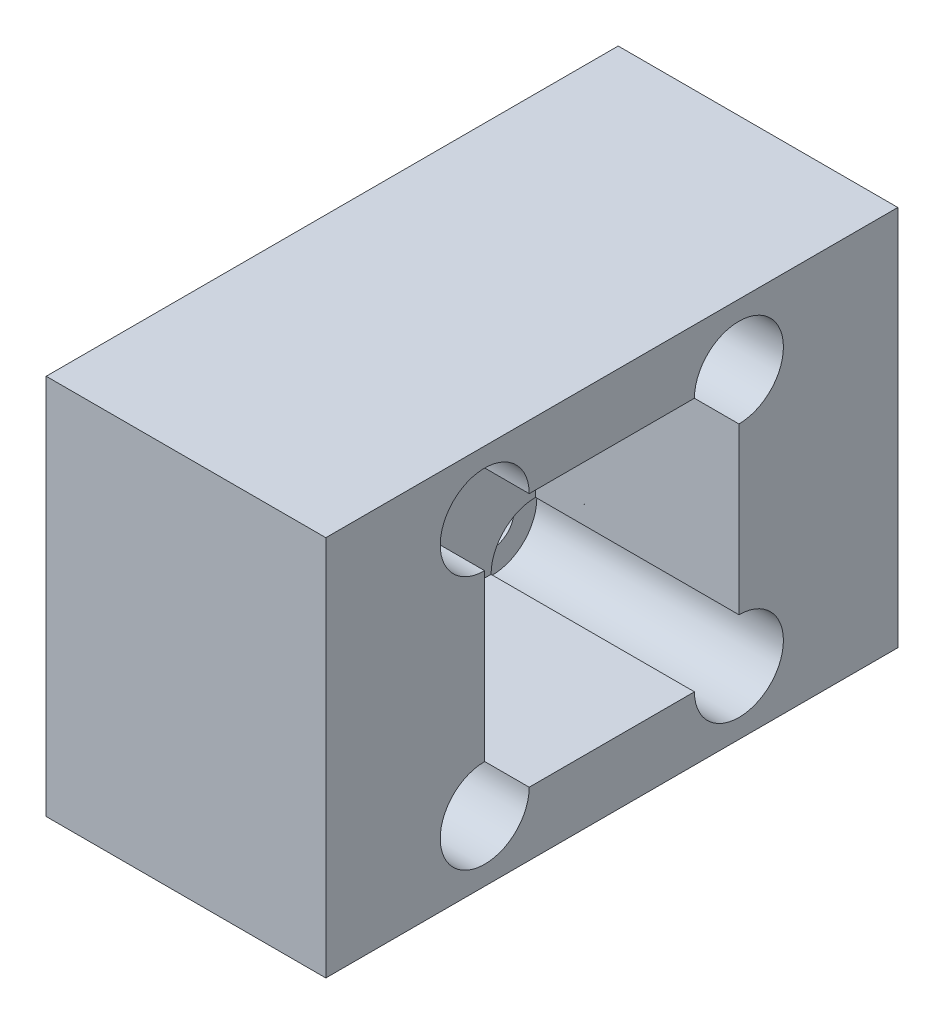
SolidWorks part; units mm, degrees
material "ABS"
ref_plane "Front Plane" through (0, 0, 0) normal (0, 0, 1) x (1, 0, 0)
ref_plane "Top Plane" through (0, 0, 0) normal (0, 1, 0) x (1, 0, 0)
ref_plane "Right Plane" through (0, 0, 0) normal (1, 0, 0) x (0, 0, -1)
sketch "Sketch1" plane through (0, 0, 0) normal (1, 0, 0) x (0, 0, -1)
  line L1 (0, 0) -> (45, 0)
  line L2 (0, 0) -> (0, 30)
  line L3 (0, 30) -> (45, 30)
  line L4 (45, 0) -> (45, 30)
  dimension "D1" = 45
  dimension "D2" = 30
extrude "Boss-Extrude1" add sketch "Sketch1" along normal blind 22
sketch "Sketch3" plane through (22, 0, 0) normal (1, 0, 0) x (0, 0, -1)
  line L0 (45, 30) -> (0, 30) construction
  line L1 (12.5, 25) -> (32.5, 25)
  line L2 (12.5, 25) -> (12.5, 5)
  line L3 (12.5, 5) -> (32.5, 5)
  line L4 (32.5, 25) -> (32.5, 5)
  line L5 (0, 30) -> (0, 0) construction
  dimension "D1" = 20
  dimension "D2" = 20
  dimension "D3" = 5
  dimension "D4" = 12.5
extrude "Cut-Extrude1" cut sketch "Sketch3" against normal blind 16
hole_wizard "CBORE for M3 Pan Head Screw4" positions "Sketch8" profile "Sketch9" counterbore size "M3" standard "ISO" end condition through all
sketch "Sketch8" plane through (22, 0, 0) normal (1, 0, 0) x (0, 0, -1)
  point P0 (12.5, 25)
  point P3 (32.5, 25)
  point P6 (32.5, 5)
  point P9 (12.5, 5)
sketch "Sketch9" plane through (22, 25, -12.5) normal (0, 1, 0) x (0, 0, -1)
  line L0 (0, 0) -> (0, 22)
  line L1 (0, 22) -> (1.7, 22)
  line L3 (1.7, 22) -> (1.7, 19.4)
  line L4 (1.7, 19.4) -> (3.5, 19.4)
  line L5 (3.5, 19.4) -> (3.5, 0)
  line L7 (3.5, 0) -> (0, 0)
  line L11 (0, -6.35) -> (0, 107.95) construction
  dimension "Thru Hole Dia." = 3.4
  dimension "Thru Hole Depth" = 22
  dimension "C'Bore Dia." = 7
  dimension "C'Bore Depth" = 19.4
mirror "Mirror1" [suppressed]
delete or keep bodies "Body-Delete/Keep 1" [suppressed] type delete bodies bodies 104
